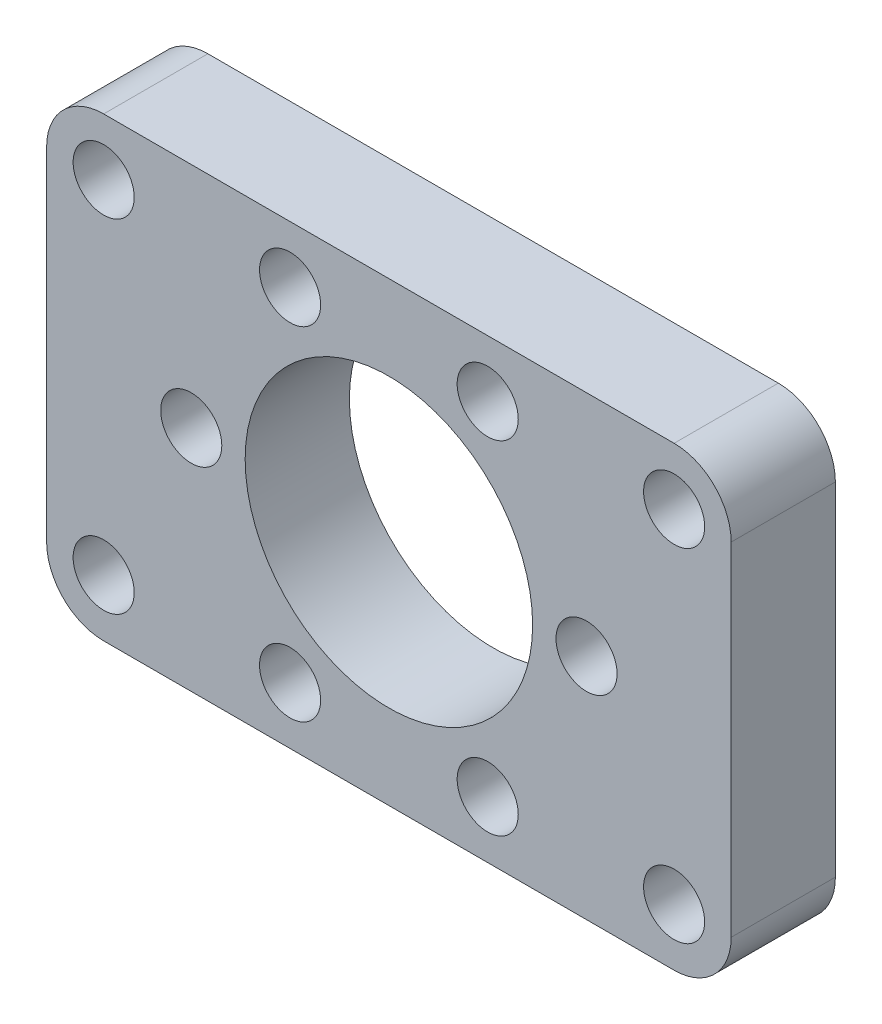
SolidWorks part; units mm, degrees
material "Acrylic (Medium-high impact)"
ref_plane "Front" through (0, 0, 0) normal (0, 0, 1) x (1, 0, 0)
ref_plane "Top" through (0, 0, 0) normal (0, 1, 0) x (1, 0, 0)
ref_plane "Right" through (0, 0, 0) normal (1, 0, 0) x (0, 0, -1)
sketch "Sketch1" plane through (0, 0, 0) normal (0, 0, 1) x (1, 0, 0)
  line L0 (0, 12.7) -> (19.05, 12.7) construction
  line L1 (0, 0) -> (38.1, 0)
  line L2 (0, 0) -> (0, 25.4)
  line L3 (0, 25.4) -> (38.1, 25.4)
  line L4 (38.1, 0) -> (38.1, 25.4)
  line L5 (19.05, 12.7) -> (19.05, 25.4) construction
  dimension "D1" = 38.1
  dimension "D2" = 25.4
extrude "Boss-Extrude1" add sketch "Sketch1" along normal blind 5.8
sketch "Sketch2" plane through (0, 0, 5.8) normal (0, 0, 1) x (1, 0, 0)
  line L0 (0, 12.7) -> (38.1, 12.7) construction
  line L1 (0, 25.4) -> (0, 0) construction
  line L2 (38.1, 0) -> (38.1, 25.4) construction
  line L3 (19.05, 25.4) -> (19.05, 0) construction
  line L4 (38.1, 25.4) -> (0, 25.4) construction
  line L5 (0, 0) -> (38.1, 0) construction
  circle A0 centre (19.05, 12.7) radius 8
  dimension "D1" = 16
extrude "Cut-Extrude1" cut sketch "Sketch2" against normal through all
hole_wizard "M3 Clearance Hole1" positions "Sketch4" profile "Sketch3" hole size "M3" standard "Ansi Metric"
sketch "Sketch4" plane through (0, 0, 5.8) normal (0, 0, 1) x (1, 0, 0)
  line L0 (19.05, 12.7) -> (30.05, 12.7) construction
  line L1 (19.05, 12.7) -> (24.55, 22.2263) construction
  line L2 (19.05, 12.7) -> (13.55, 22.2263) construction
  line L3 (19.05, 12.7) -> (8.05, 12.7) construction
  line L4 (19.05, 12.7) -> (13.55, 3.1737) construction
  line L5 (19.05, 12.7) -> (24.55, 3.1737) construction
  point P0 (30.05, 12.7)
  point P9 (24.55, 22.2263)
  point P12 (13.55, 22.2263)
  point P15 (8.05, 12.7)
  point P18 (13.55, 3.1737)
  point P21 (24.55, 3.1737)
  dimension "D1" = 11
  dimension "D2" = 6
sketch "Sketch3" plane through (30.05, 12.7, 5.8) normal (1, 0, 0) x (0, -1, 0)
  line L0 (0, 0) -> (0, 7.3715)
  line L1 (0, 7.3715) -> (1.7, 6.35)
  line L2 (1.7, 6.35) -> (1.7, 0)
  line L5 (1.7, 0) -> (0, 0)
  line L10 (0, 7.3715) -> (-1.7, 6.35) construction
  line L11 (0, -6.35) -> (0, 107.95) construction
  dimension "Hole Dia." = 3.4
  dimension "Hole Depth" = 6.35
  dimension "Drill Angle" = 118
hole_wizard "M3 Clearance Hole2" positions "Sketch6" profile "Sketch5" hole size "M3" standard "Ansi Metric"
sketch "Sketch6" plane through (0, 0, 5.8) normal (0, 0, 1) x (1, 0, 0)
  line L0 (19.05, 12.7) -> (19.05, 25.4) construction
  line L1 (38.1, 25.4) -> (0, 25.4) construction
  line L3 (19.05, 12.7) -> (0, 12.7) construction
  line L4 (0, 25.4) -> (0, 0) construction
  line L6 (3.175, 22.225) -> (3.175, 12.7) construction
  point P0 (3.175, 22.225)
  point P18 (34.925, 22.225)
  point P20 (34.925, 3.175)
  point P21 (3.175, 3.175)
  dimension "D1" = 3.175
  dimension "D2" = 3.175
sketch "Sketch5" plane through (3.175, 22.225, 5.8) normal (1, 0, 0) x (0, -1, 0)
  line L0 (0, 0) -> (0, 7.3715)
  line L1 (0, 7.3715) -> (1.7, 6.35)
  line L2 (1.7, 6.35) -> (1.7, 0)
  line L5 (1.7, 0) -> (0, 0)
  line L10 (0, 7.3715) -> (-1.7, 6.35) construction
  line L11 (0, -6.35) -> (0, 107.95) construction
  dimension "Hole Dia." = 3.4
  dimension "Hole Depth" = 6.35
  dimension "Drill Angle" = 118
fillet "Fillet1" radius 3.175 4 edges at (0, 0, 2.9) (0, 25.4, 2.9) (38.1, 25.4, 2.9) (38.1, 0, 2.9)
other "Move Face1" [suppressed] parameters "D1"=0.2
